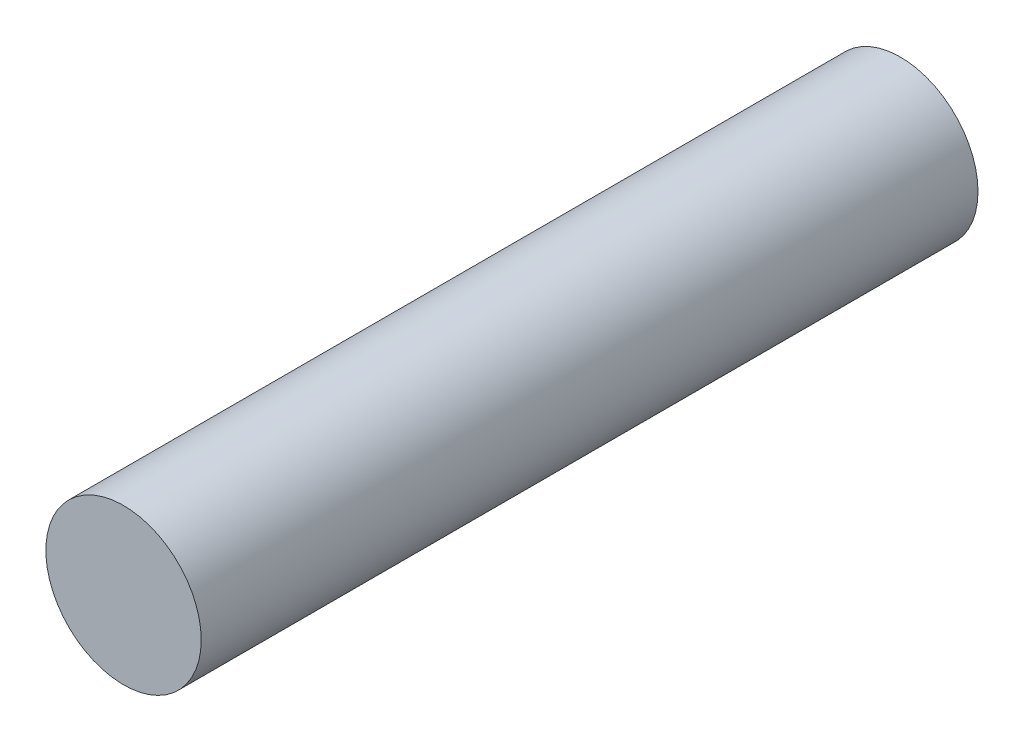
SolidWorks part; units mm, degrees
ref_plane "前视基准面" through (0, 0, 0) normal (0, 0, 1) x (1, 0, 0)
ref_plane "上视基准面" through (0, 0, 0) normal (0, 1, 0) x (1, 0, 0)
ref_plane "右视基准面" through (0, 0, 0) normal (1, 0, 0) x (0, 0, -1)
sketch "草图1" plane through (0, 0, 0) normal (0, 0, 1) x (1, 0, 0)
  circle A0 centre (0, 0) radius 5
  dimension "D1" = 10
extrude "凸台-拉伸1" add sketch "草图1" along normal blind 50
ref_point "点1"
